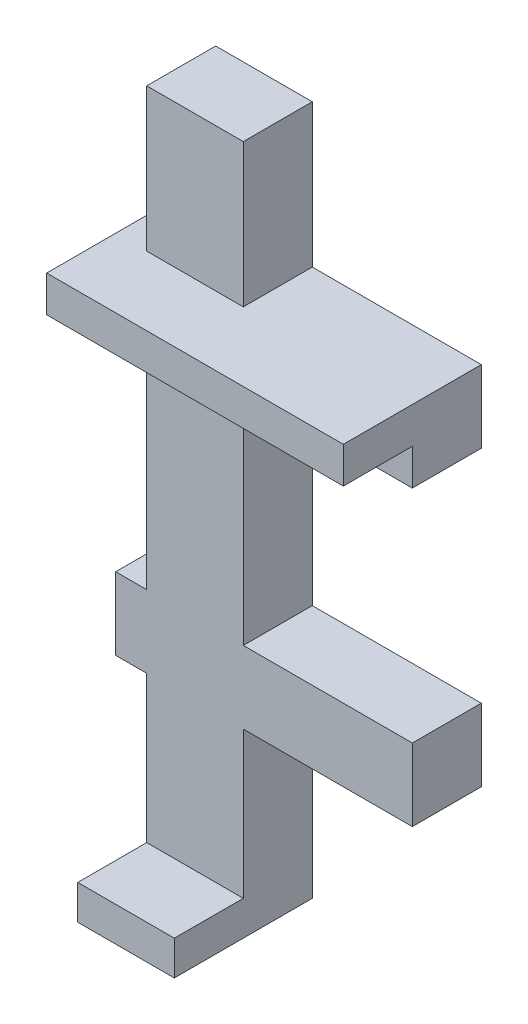
SolidWorks part; units mm, degrees
ref_plane "Front Plane" through (0, 0, 0) normal (0, 0, 1) x (1, 0, 0)
ref_plane "Top Plane" through (0, 0, 0) normal (0, 1, 0) x (1, 0, 0)
ref_plane "Right Plane" through (0, 0, 0) normal (1, 0, 0) x (0, 0, -1)
sketch "Sketch1" plane through (0, 0, 0) normal (0, 0, 1) x (1, 0, 0)
  line L1 (-2.8, -20) -> (2.8, -20)
  line L2 (-2.8, -20) -> (-2.8, 20)
  line L3 (-2.8, 20) -> (2.8, 20)
  line L4 (2.8, -20) -> (2.8, 20)
  line L5 (-2.8, -20) -> (2.8, 20) construction
  line L6 (-2.8, 20) -> (2.8, -20) construction
  point P0 (0, 0)
  dimension "D1" = 40
  dimension "D2" = 5.6
extrude "Boss-Extrude1" add sketch "Sketch1" along normal blind 4 contours L4 L3 L2 L1
sketch "Sketch2" plane through (0, 0, 4) normal (0, 0, 1) x (1, 0, 0)
  line L0 (2.8, -20) -> (2.8, 20) construction
  line L1 (-2.8, -20) -> (2.8, -20)
  line L2 (-2.8, -20) -> (-2.8, -18)
  line L3 (-2.8, -18) -> (2.8, -18)
  line L4 (2.8, -20) -> (2.8, -18)
  dimension "D1" = 2
extrude "Boss-Extrude2" add sketch "Sketch2" along normal blind 4
sketch "Sketch4" plane through (-2.8, 0, 0) normal (-1, 0, 0) x (0, 0, 1)
  line L0 (0, -20) -> (0, 20) construction
  line L1 (0, 11.7) -> (4, 11.7)
  line L2 (0, 11.7) -> (0, 7.5)
  line L3 (0, 7.5) -> (4, 7.5)
  line L4 (4, 11.7) -> (4, 7.5)
  line L5 (4, -18) -> (4, 20) construction
  line L6 (8, -20) -> (0, -20) construction
  dimension "D1" = 4.2
  dimension "D2" = 27.5
extrude "Boss-Extrude3" add sketch "Sketch4" along normal blind 1.8
ref_plane "Plane1" through (0, 0, 0) normal (-1, 0, 0) x (0, 0, 1)
mirror "Mirror1" about plane through (0, 0, 0) normal (-1, 0, 0) of "Boss-Extrude3"
sketch "Sketch6" plane through (0, 0, 4) normal (0, 0, 1) x (1, 0, 0)
  line L0 (2.8, 1.1) -> (-2.8, 1.1) construction
  line L1 (2.8, -18) -> (2.8, 7.5) construction
  line L2 (-2.8, -18) -> (-2.8, 7.5) construction
  line L3 (2.8, -18) -> (-2.8, -18) construction
  line L4 (4.6, 7.5) -> (2.8, 7.5) construction
  dimension "D1" = 19.1
  dimension "D2" = 6.4
sketch "Sketch7" plane through (-2.8, 0, 0) normal (-1, 0, 0) x (0, 0, 1)
  line L0 (4, 1.1) -> (0, 1.1) construction
  line L1 (4, -18) -> (4, 7.5) construction
  line L2 (0, -20) -> (0, 7.5) construction
  line L3 (8, -18) -> (4, -18) construction
  dimension "D1" = 19.1
ref_plane "Plane3" through (0, 1.1, 0) normal (0, -1, 0) x (-1, 0, 0)
mirror "Mirror2" about plane through (0, 1.1, 0) normal (0, -1, 0) of "Mirror1", "Boss-Extrude3"
sketch "Sketch8" plane through (4.6, 0, 0) normal (1, 0, 0) x (0, 0, -1)
  line L1 (-4, 11.7) -> (0, 11.7)
  line L2 (-4, 11.7) -> (-4, 7.5)
  line L3 (-4, 7.5) -> (0, 7.5)
  line L4 (0, 11.7) -> (0, 7.5)
  line L5 (-4, -5.3) -> (0, -5.3)
  line L6 (-4, -5.3) -> (-4, -9.5)
  line L7 (-4, -9.5) -> (0, -9.5)
  line L8 (0, -5.3) -> (0, -9.5)
extrude "Boss-Extrude4" add sketch "Sketch8" along normal blind 8
sketch "Sketch9" plane through (0, 0, 4) normal (0, 0, 1) x (1, 0, 0)
  line L0 (12.6, 11.7) -> (12.6, 7.5) construction
  line L1 (-4.6, 11.7) -> (12.6, 11.7)
  line L2 (-4.6, 11.7) -> (-4.6, 9.6)
  line L3 (-4.6, 9.6) -> (12.6, 9.6)
  line L4 (12.6, 11.7) -> (12.6, 9.6)
extrude "Boss-Extrude5" add sketch "Sketch9" along normal blind 4
